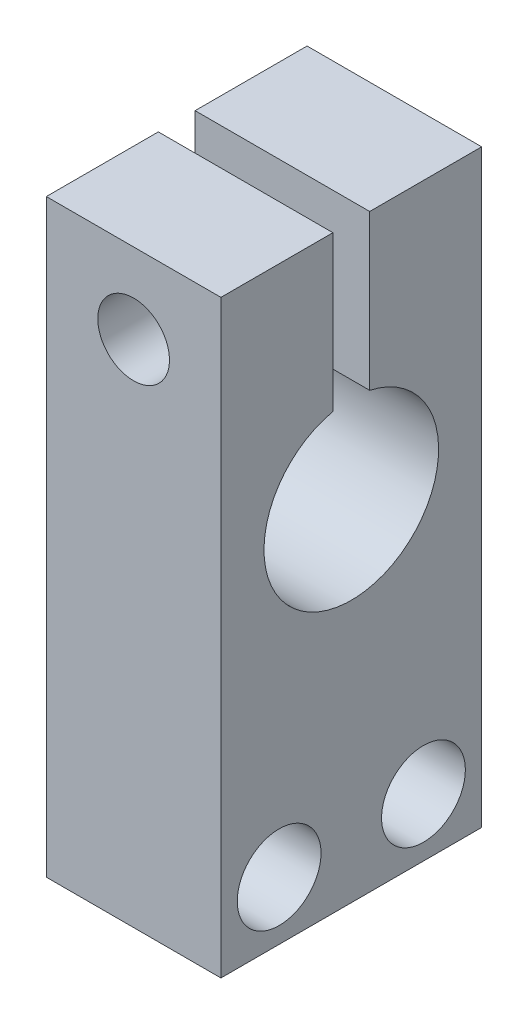
SolidWorks part; units mm, degrees
ref_plane "Front Plane" through (0, 0, 0) normal (0, 0, 1) x (1, 0, 0)
ref_plane "Top Plane" through (0, 0, 0) normal (0, 1, 0) x (1, 0, 0)
ref_plane "Right Plane" through (0, 0, 0) normal (1, 0, 0) x (0, 0, -1)
ref_plane "Plane1" through (4.7625, 0, 0) normal (1, 0, 0) x (0, 0, -1)
sketch "Sketch1" plane through (4.7625, 0, 0) normal (1, 0, 0) x (0, 0, -1)
  line L0 (15.875, -19.05) -> (15.875, 13.1064)
  line L1 (15.875, 13.1064) -> (-15.875, 13.1064)
  line L2 (-15.875, 13.1064) -> (-15.875, -19.05)
  line L3 (-15.875, -19.05) -> (15.875, -19.05)
  point P7 (-15.875, -4.0478)
  dimension "D1" = 31.75
  dimension "D2" = 32.1564
  dimension "D3" = 13.1064
  dimension "D4" = 15.875
extrude "Boss-Extrude1" add sketch "Sketch1" against normal blind 9.525
sketch "Sketch2" plane through (-4.7625, 0, 0) normal (-1, 0, 0) x (0, 0, 1)
  line L0 (-7.112, -19.05) -> (-7.112, 13.1064)
  line L1 (-7.112, 13.1064) -> (-15.875, 13.1064)
  line L2 (-15.875, 13.1064) -> (-15.875, -19.05)
  line L3 (-15.875, -19.05) -> (-7.112, -19.05)
  line L4 (15.875, -19.05) -> (-15.875, -19.05) construction
  line L5 (-15.875, 13.1064) -> (15.875, 13.1064) construction
  line L6 (-15.875, -19.05) -> (-15.875, 13.1064) construction
  dimension "D1" = 8.763
extrude "Cut-Extrude1" cut sketch "Sketch2" against normal through all
sketch "Sketch3" plane through (-4.7625, 0, 0) normal (-1, 0, 0) x (0, 0, 1)
  line L0 (1.0033, 13.1064) -> (-1.0033, 13.1064)
  line L1 (-1.0033, 13.1064) -> (-1.0033, 4.6556)
  line L2 (1.0033, 4.6556) -> (1.0033, 13.1064)
  line L3 (-7.112, -19.05) -> (-7.112, 13.1064) construction
  line L4 (-7.112, 13.1064) -> (15.875, 13.1064) construction
  arc A0 (-1.0033, 4.6556) -> (1.0033, 4.6556) centre (0, 0) cw
  dimension "D1" = 4.7625
  dimension "D2" = 6.1087
  dimension "D3" = 7.112
  dimension "D4" = 8.4508
extrude "Cut-Extrude2" cut sketch "Sketch3" against normal through all
sketch "Sketch4" plane through (-4.7625, 0, 0) normal (-1, 0, 0) x (0, 0, 1)
  line L0 (7.112, -19.0536) -> (15.875, -19.0536)
  line L1 (15.875, -19.0536) -> (15.875, 13.1064)
  line L2 (15.875, 13.1064) -> (7.112, 13.1064)
  line L3 (7.112, 13.1064) -> (7.112, -19.0536)
  line L4 (1.0033, 4.6556) -> (1.0033, 13.1064) construction
  line L5 (1.0033, 13.1064) -> (15.875, 13.1064) construction
  dimension "D1" = 6.1087
  dimension "D2" = 14.8717
  dimension "D3" = 32.16
extrude "Cut-Extrude3" cut sketch "Sketch4" against normal through all
sketch "Sketch5" plane through (0, 0, 0) normal (0, 0, 1) x (1, 0, 0)
  line L0 (-4.7625, 4.7625) -> (-4.7625, 0)
  line L1 (-4.7625, 0) -> (4.7625, 0)
  line L2 (4.7625, 0) -> (4.7625, 4.7625)
  line L3 (4.7625, 4.7625) -> (-4.7625, 4.7625)
  line L4 (-4.7625, 0) -> (4.7625, 0) construction
  dimension "D1" = 4.7625
  dimension "D2" = 4.7625
  dimension "D3" = 4.7625
revolve "Cut-Revolve1" cut sketch "Sketch5" angle 360 about L4
hole_wizard "Hole1" positions "Sketch7" profile "Sketch6" legacy
sketch "Sketch7" plane through (0, 0, 1.0033) normal (0, 0, -1) x (-1, 0, 0)
  point P0 (0, 8.7376)
sketch "Sketch6" plane through (0, 8.7376, 1.0033) normal (1, 0, 0) x (0, 1, 0)
  line L0 (0, 0) -> (0, 6.1087)
  line L1 (0, 6.1087) -> (1.3208, 6.1087)
  line L2 (1.3208, 6.1087) -> (1.3208, 0)
  line L3 (1.3208, 0) -> (0, 0)
  line L4 (0, 110) -> (0, -10) construction
  dimension "Diameter" = 2.6416
  dimension "Depth" = 6.1087
hole_wizard "CBORE for M3.5 Hex Head Machine Screw1" positions "Sketch9" profile "Sketch8" counterbore size "M3.5" standard "ANSI Metric"
sketch "Sketch9" plane through (0, 0, -7.112) normal (0, 0, -1) x (-1, 0, 0)
  point P0 (0, 8.7376)
sketch "Sketch8" plane through (0, 8.7376, -7.112) normal (1, 0, 0) x (0, 1, 0)
  line L0 (0, 0) -> (0, 14.224)
  line L1 (0, 14.224) -> (1.9558, 14.224)
  line L3 (1.9558, 14.224) -> (1.9558, 3.9116)
  line L4 (1.9558, 3.9116) -> (3.5687, 3.9116)
  line L5 (3.5687, 3.9116) -> (3.5687, 0)
  line L7 (3.5687, 0) -> (0, 0)
  line L11 (0, -6.35) -> (0, 107.95) construction
  dimension "Thru Hole Dia." = 3.9116
  dimension "Thru Hole Depth" = 14.224
  dimension "C'Bore Dia." = 7.1374
  dimension "C'Bore Depth" = 3.9116
hole_wizard "M4 Clearance Hole1" positions "Sketch11" profile "Sketch10" hole size "M4" standard "ANSI Metric"
sketch "Sketch11" plane through (4.7625, -17.4625, 0) normal (-1, 0, 0) x (0, 1, 0)
  line L3 (-1.5875, -7.112) -> (-1.5875, 7.112) construction
  line L4 (-1.5875, 7.112) -> (30.5689, 7.112) construction
  line L5 (30.5689, -7.112) -> (-1.5875, -7.112) construction
  point P2 (1.5875, 3.937)
  point P4 (1.5875, -3.937)
  point P21 (0.3975, 4.6369)
  dimension "D1" = 3.175
  dimension "D2" = 3.175
  dimension "D3" = 3.175
sketch "Sketch10" plane through (4.7625, -15.875, -3.937) normal (0, 1, 0) x (0, 0, -1)
  line L0 (0, 0) -> (0, 9.525)
  line L1 (0, 9.525) -> (2.286, 9.525)
  line L2 (2.286, 9.525) -> (2.286, 0)
  line L5 (2.286, 0) -> (0, 0)
  line L11 (0, -6.35) -> (0, 107.95) construction
  dimension "Thru Hole Dia." = 4.572
  dimension "Thru Hole Depth" = 9.525
